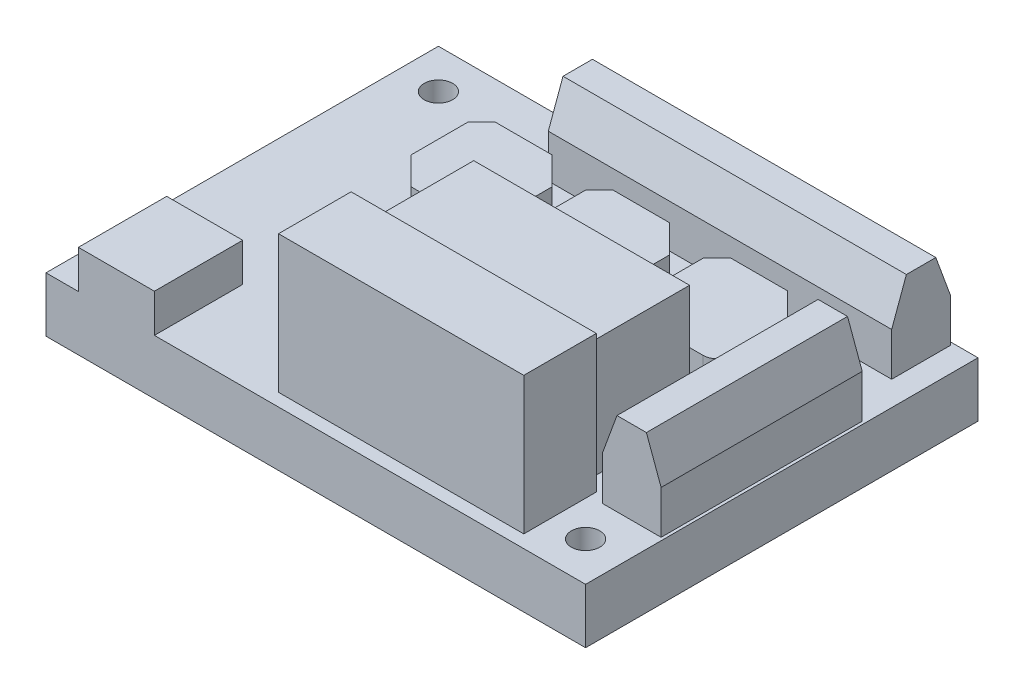
SolidWorks part; units mm, degrees
ref_plane "Front Plane" through (0, 0, 0) normal (0, 0, 1) x (1, 0, 0)
ref_plane "Top Plane" through (0, 0, 0) normal (0, 1, 0) x (1, 0, 0)
ref_plane "Right Plane" through (0, 0, 0) normal (1, 0, 0) x (0, 0, -1)
sketch "Sketch1" plane through (0, 0, 0) normal (0, 1, 0) x (1, 0, 0)
  line L1 (-27.5, -20) -> (27.5, -20)
  line L2 (-27.5, -20) -> (-27.5, 20)
  line L3 (-27.5, 20) -> (27.5, 20)
  line L4 (27.5, -20) -> (27.5, 20)
  line L5 (-27.5, -20) -> (27.5, 20) construction
  line L6 (-27.5, 20) -> (27.5, -20) construction
  point P0 (0, 0)
  dimension "D1" = 40
  dimension "D2" = 55
extrude "Boss-Extrude1" add sketch "Sketch1" along normal blind 5.6
hole_wizard "M2.5 Clearance Hole1" positions "Sketch4" profile "Sketch3" hole size "M2.5" standard "Ansi Metric" end condition through all
sketch "Sketch4" plane through (0, 5.6, 0) normal (0, 1, 0) x (-1, 0, 0)
  line L1 (23.5, -16) -> (-23.5, -16) construction
  line L2 (23.5, -16) -> (23.5, 16) construction
  line L3 (23.5, 16) -> (-23.5, 16) construction
  line L4 (-23.5, -16) -> (-23.5, 16) construction
  line L5 (-23.5, -16) -> (23.5, 16) construction
  point P0 (23.5, -16)
  point P1 (-23.5, 16)
  dimension "D1" = 32
  dimension "D2" = 47
sketch "Sketch3" plane through (-23.5, 5.6, -16) normal (1, 0, 0) x (0, 0, 1)
  line L0 (0, 0) -> (0, 5.6)
  line L1 (0, 5.6) -> (1.45, 5.6)
  line L2 (1.45, 5.6) -> (1.45, 0)
  line L5 (1.45, 0) -> (0, 0)
  line L11 (0, -6.35) -> (0, 107.95) construction
  dimension "Thru Hole Dia." = 2.9
  dimension "Thru Hole Depth" = 5.6
sketch "Sketch5" plane through (0, 5.6, 0) normal (0, 1, 0) x (1, 0, 0)
  line L0 (27.5, -20) -> (27.5, 20) construction
  line L1 (19.9, -11.3) -> (-5.1, -11.3)
  line L2 (19.9, -11.3) -> (19.9, -18.7)
  line L3 (19.9, -18.7) -> (-5.1, -18.7)
  line L4 (-5.1, -11.3) -> (-5.1, -18.7)
  line L5 (-27.5, -20) -> (27.5, -20) construction
  dimension "D1" = 7.4
  dimension "D2" = 25
  dimension "D3" = 7.6
  dimension "D4" = 1.3
extrude "Boss-Extrude2" add sketch "Sketch5" along normal offset from surface (14 mm away) 19.6 up to face at (-23.5, 0, -14.55)
sketch "Sketch6" plane through (0, 5.6, 0) normal (0, 1, 0) x (1, 0, 0)
  line L0 (-27.5, -20) -> (27.5, -20) construction
  line L1 (21.2, 8.5) -> (27.2, 8.5)
  line L2 (21.2, 8.5) -> (21.2, -12)
  line L3 (21.2, -12) -> (27.2, -12)
  line L4 (27.2, 8.5) -> (27.2, -12)
  line L5 (27.5, -20) -> (27.5, 20) construction
  dimension "D1" = 20.5
  dimension "D2" = 6
  dimension "D3" = 8
  dimension "D4" = 0.3
extrude "Boss-Extrude3" add sketch "Sketch6" along normal blind 8.5
sketch "Sketch7" plane through (0, 0, 12) normal (0, 0, 1) x (1, 0, 0)
  line L1 (21.2, 14.1) -> (27.2, 14.1) construction
  line L2 (25.7, 14.1) -> (27.2, 10)
  line L3 (27.2, 14.1) -> (27.2, 5.6) construction
  line L4 (27.2, 10) -> (27.2, 14.1)
  line L5 (27.2, 14.1) -> (25.7, 14.1)
  line L6 (22.7, 14.1) -> (21.2, 10)
  line L7 (21.2, 14.1) -> (21.2, 5.6) construction
  line L8 (21.2, 10) -> (21.2, 14.1)
  line L9 (21.2, 14.1) -> (22.7, 14.1)
  dimension "D1" = 3
  dimension "D2" = 4.4
extrude "Cut-Extrude1" cut sketch "Sketch7" against normal up to next
sketch "Sketch8" plane through (0, 5.6, 0) normal (0, 1, 0) x (-1, 0, 0)
  line L0 (-27.5, -20) -> (27.5, -20) construction
  line L1 (-25, -19.7) -> (10, -19.7)
  line L2 (-25, -19.7) -> (-25, -13.7)
  line L3 (-25, -13.7) -> (10, -13.7)
  line L4 (10, -19.7) -> (10, -13.7)
  line L5 (-27.5, 20) -> (-27.5, -20) construction
  dimension "D1" = 6
  dimension "D2" = 35
  dimension "D3" = 0.3
  dimension "D4" = 2.5
extrude "Boss-Extrude4" add sketch "Sketch8" along normal up to surface (8.5 mm away) up to face at (24.2, 14.1, 1.75)
sketch "Sketch9" plane through (25, 0, 0) normal (1, 0, 0) x (0, 0, -1)
  line L2 (18.2, 14.1) -> (19.7, 10)
  line L4 (19.7, 10) -> (19.7, 14.1)
  line L5 (19.7, 14.1) -> (18.2, 14.1)
  line L6 (15.2, 14.1) -> (13.7, 10)
  line L8 (13.7, 10) -> (13.7, 14.1)
  line L9 (13.7, 14.1) -> (15.2, 14.1)
  dimension "D1" = 3
  dimension "D2" = 4.4
extrude "Cut-Extrude2" cut sketch "Sketch9" against normal up to next
sketch "Sketch10" plane through (0, 5.6, 0) normal (0, 1, 0) x (1, 0, 0)
  line L0 (19.9, -11.3) -> (-5.1, -11.3) construction
  line L1 (18.4, -9.8) -> (-3.6, -9.8)
  line L2 (18.4, -9.8) -> (18.4, -0.3)
  line L3 (18.4, -0.3) -> (-3.6, -0.3)
  line L4 (-3.6, -9.8) -> (-3.6, -0.3)
  line L5 (7.4, -9.8) -> (7.4, -11.3) construction
  dimension "D1" = 22
  dimension "D2" = 9.5
  dimension "D3" = 1.5
extrude "Boss-Extrude5" add sketch "Sketch10" along normal blind 12
sketch "Sketch11" plane through (0, 5.6, 0) normal (0, 1, 0) x (-1, 0, 0)
  line L0 (-19.2, -3.1142) -> (-19.2, -8.8716)
  line L1 (-19.2, -8.8716) -> (-16.3716, -11.7)
  line L2 (-16.3716, -11.7) -> (-10.6142, -11.7)
  line L3 (-10.6142, -11.7) -> (-9.2, -10.2858)
  line L4 (-9.2, -10.2858) -> (-9.2, -4.5284)
  line L5 (-9.2, -4.5284) -> (-12.0284, -1.7)
  line L6 (-12.0284, -1.7) -> (-17.7858, -1.7)
  line L7 (-21.2, -8.5) -> (-21.2, 12) construction
  line L8 (-18.4, 0.3) -> (3.6, 0.3) construction
  arc A0 (-19.2, -3.1142) -> (-17.7858, -1.7) centre (-17.7858, -3.1142) cw
  point P9 (-17.7858, -10.2858)
  dimension "D1" = 10
  dimension "D2" = 10
  dimension "D3" = 4
  dimension "D4" = 2
  dimension "D5" = 45
  dimension "D6" = 2
  dimension "D7" = 2
extrude "Boss-Extrude6" add sketch "Sketch11" along normal blind 4.5
pattern_linear "LPattern1" count 3 spacing 12 along (-1, 0, 0) of "Boss-Extrude6"
sketch "Sketch12" plane through (0, 5.6, 0) normal (0, 1, 0) x (-1, 0, 0)
  line L1 (24.2, 20) -> (16.45, 20)
  line L2 (24.2, 20) -> (24.2, 11)
  line L3 (24.2, 11) -> (16.45, 11)
  line L4 (16.45, 20) -> (16.45, 11)
  line L5 (27.5, 20) -> (-27.5, 20) construction
  line L6 (27.5, -20) -> (27.5, 20) construction
  dimension "D1" = 7.75
  dimension "D2" = 9
  dimension "D3" = 3.3
extrude "Boss-Extrude7" add sketch "Sketch12" along normal blind 3.9
